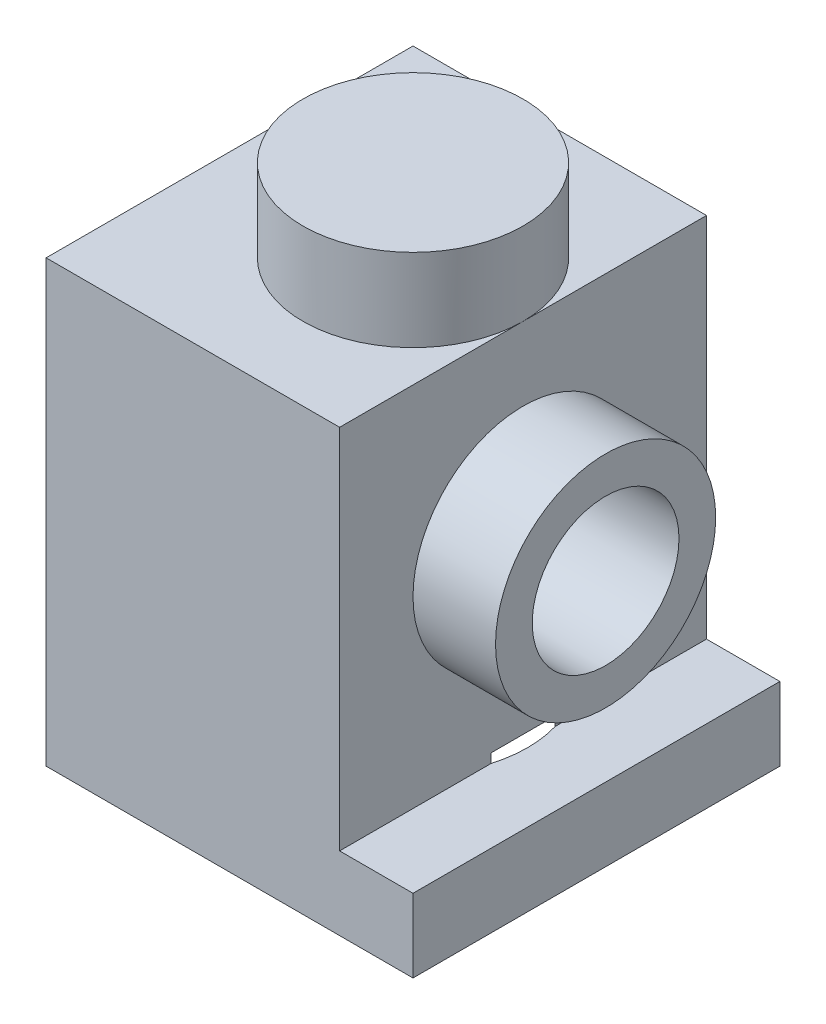
SolidWorks part; units mm, degrees
ref_plane "Спереди" through (0, 0, 0) normal (0, 0, 1) x (1, 0, 0)
ref_plane "Сверху" through (0, 0, 0) normal (0, 1, 0) x (1, 0, 0)
ref_plane "Справа" through (0, 0, 0) normal (1, 0, 0) x (0, 0, -1)
sketch "Эскиз1" plane through (0, 0, 0) normal (0, 1, 0) x (1, 0, 0)
  line L1 (4, -4) -> (-4, -4)
  line L2 (4, -4) -> (4, 4)
  line L3 (4, 4) -> (-4, 4)
  line L4 (-4, -4) -> (-4, 4)
  line L5 (4, -4) -> (-4, 4) construction
  line L6 (4, 4) -> (-4, -4) construction
  point P0 (0, 0)
  dimension "D1" = 8
  dimension "D2" = 8
extrude "Бобышка-Вытянуть1" add sketch "Эскиз1" along normal blind 9.6
sketch "Эскиз2" plane through (0, 9.6, 0) normal (0, 1, 0) x (1, 0, 0)
  line L0 (4, 4) -> (-4, 4) construction
  line L1 (2.4, 4) -> (4, 4)
  line L2 (2.4, 4) -> (2.4, -4)
  line L3 (2.4, -4) -> (4, -4)
  line L4 (4, 4) -> (4, -4)
  dimension "D1" = 1.6
extrude "Вырез-Вытянуть1" cut sketch "Эскиз2" against normal blind 8
sketch "Эскиз5" plane through (2.4, 0, 0) normal (1, 0, 0) x (0, 0, -1)
  line L0 (-4, 9.6) -> (4, 1.6)
  line L1 (4, 1.6) -> (-4, 1.6) construction
  line L2 (4, 9.6) -> (-4, 1.6)
  circle A0 centre (0, 5.6) radius 2.4
  circle A1 centre (0, 5.6) radius 1.6
extrude "Бобышка-Вытянуть2" add sketch "Эскиз5" along normal blind 1.8 contours A0
sketch "Эскиз8" plane through (4.2, 0, 0) normal (1, 0, 0) x (0, 0, -1)
  circle A0 centre (0, 5.6) radius 1.6
extrude "Вырез-Вытянуть3" cut sketch "Эскиз8" against normal blind 9
sketch "Эскиз9" plane through (0, 9.6, 0) normal (0, 1, 0) x (1, 0, 0)
  line L0 (-4, 4) -> (-4, -4) construction
  circle A1 centre (0, 0) radius 2.4
  dimension "D1" = 4
extrude "Бобышка-Вытянуть3" add sketch "Эскиз9" along normal blind 1.8
sketch "Эскиз10" plane through (-4, 0, 0) normal (-1, 0, 0) x (0, 0, 1)
  line L0 (2.4, 9.6) -> (2.4, 0)
  line L1 (-4, 0) -> (4, 0) construction
  line L2 (-2.4, 9.6) -> (-2.4, 0)
sketch "Эскиз11" plane through (-4, 0, 0) normal (-1, 0, 0) x (0, 0, 1)
  circle A0 centre (0, 5.6) radius 2.4
sketch "Эскиз13" plane through (-4, 0, 0) normal (-1, 0, 0) x (0, 0, 1)
  line L0 (-2.4, 9.6) -> (-2.4, 0) construction
  line L1 (2.4, 3.1983) -> (-2.4, 3.1983)
  line L2 (2.4, 3.1983) -> (2.4, 8.0017)
  line L3 (2.4, 8.0017) -> (-2.4, 8.0017)
  line L4 (-2.4, 3.1983) -> (-2.4, 8.0017)
  line L5 (2.4, 3.1983) -> (-2.4, 8.0017) construction
  line L6 (2.4, 8.0017) -> (-2.4, 3.1983) construction
  point P0 (0, 5.6)
extrude "Вырез-Вытянуть4" cut sketch "Эскиз13" against normal blind 5
sketch "Эскиз14" plane through (0, 0, 0) normal (0, -1, 0) x (1, 0, 0)
  line L1 (2.8813, -2.6885) -> (-2.8813, -2.6885)
  line L2 (2.8813, -2.6885) -> (2.8813, 2.6885)
  line L3 (2.8813, 2.6885) -> (-2.8813, 2.6885)
  line L4 (-2.8813, -2.6885) -> (-2.8813, 2.6885)
  line L5 (2.8813, -2.6885) -> (-2.8813, 2.6885) construction
  line L6 (2.8813, 2.6885) -> (-2.8813, -2.6885) construction
  point P0 (0, 0)
sketch "Эскиз15" plane through (0, 0, 0) normal (0, -1, 0) x (1, 0, 0)
  circle A0 centre (0, 0) radius 2.5
extrude "Вырез-Вытянуть5" cut sketch "Эскиз15" against normal blind 1.8
